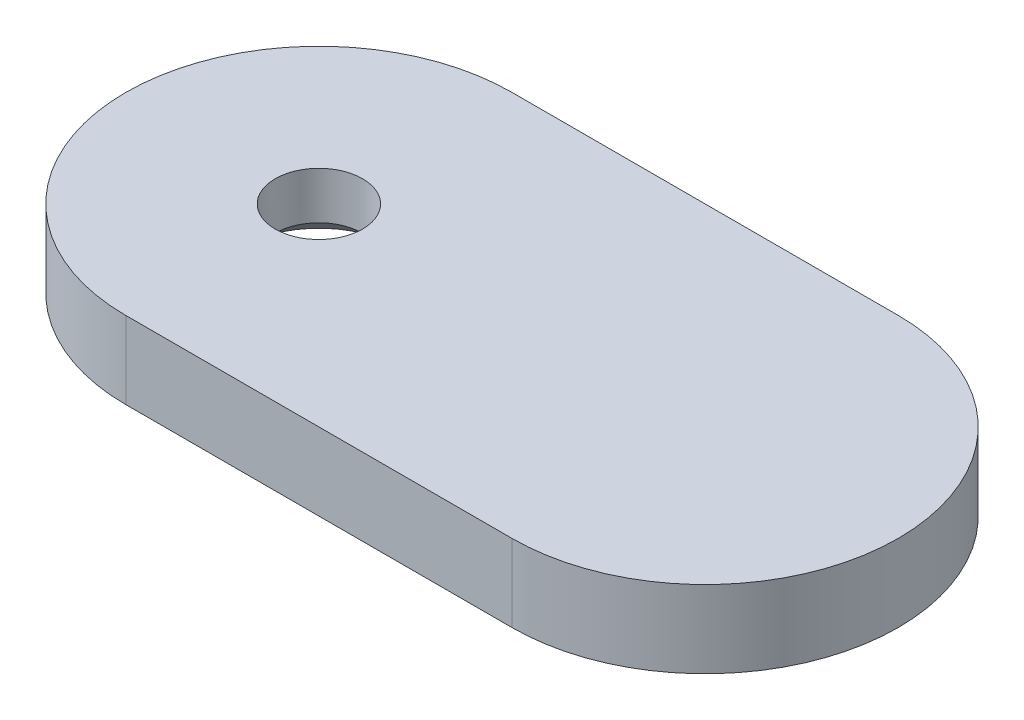
SolidWorks part; units mm, degrees
ref_plane "Front Plane" through (0, 0, 0) normal (0, 0, 1) x (1, 0, 0)
ref_plane "Top Plane" through (0, 0, 0) normal (0, 1, 0) x (1, 0, 0)
ref_plane "Right Plane" through (0, 0, 0) normal (1, 0, 0) x (0, 0, -1)
sketch "Sketch1" plane through (0, 0, 0) normal (0, 1, 0) x (1, 0, 0)
  line L0 (-6.9208, 0) -> (3.0792, 0) construction
  line L1 (-6.9208, 5) -> (3.0792, 5)
  line L2 (-6.9208, -5) -> (3.0792, -5)
  arc A0 (-6.9208, 5) -> (-6.9208, -5) centre (-6.9208, 0) ccw
  arc A1 (3.0792, -5) -> (3.0792, 5) centre (3.0792, 0) ccw
  point P2 (-1.9208, 0)
  dimension "D1" = 5
  dimension "D2" = 10
extrude "Boss-Extrude1" add sketch "Sketch1" along normal blind 2
hole_wizard "#4-40 Tapped Hole4" positions "Sketch8" profile "Sketch9" tap size "#4-40" standard "ANSI Inch"
sketch "Sketch8" plane through (-19.6321, 0, 165.6812) normal (0, -1, 0) x (0.5683, 0, -0.8228)
  point P0 (143.5471, -83.7024)
sketch "Sketch9" plane through (-6.9208, 0, 0) normal (1, 0, 0) x (0, 0, -1)
  line L0 (0, 0) -> (0, 30.6792)
  line L1 (0, 30.6792) -> (1.1303, 30)
  line L2 (1.1303, 30) -> (1.1303, 0.7779)
  line L3 (1.1303, 0.7779) -> (2.0574, 0)
  line L4 (2.0574, 0) -> (0, 0)
  line L5 (-1.1303, 0.7779) -> (-2.0574, 0) construction
  line L6 (0, 30.6792) -> (-1.1303, 30) construction
  line L7 (0, -6.35) -> (0, 107.95) construction
  dimension "Tap Drill Dia." = 2.2606
  dimension "Tap Drill Depth" = 30
  dimension "Near C'Sink Dia." = 4.1148
  dimension "Near C'Sink Angle" = 100
  dimension "Drill Angle" = 118
cosmetic thread "Hole Thread4" parameters "D1"=2, "D2"=2.8448
